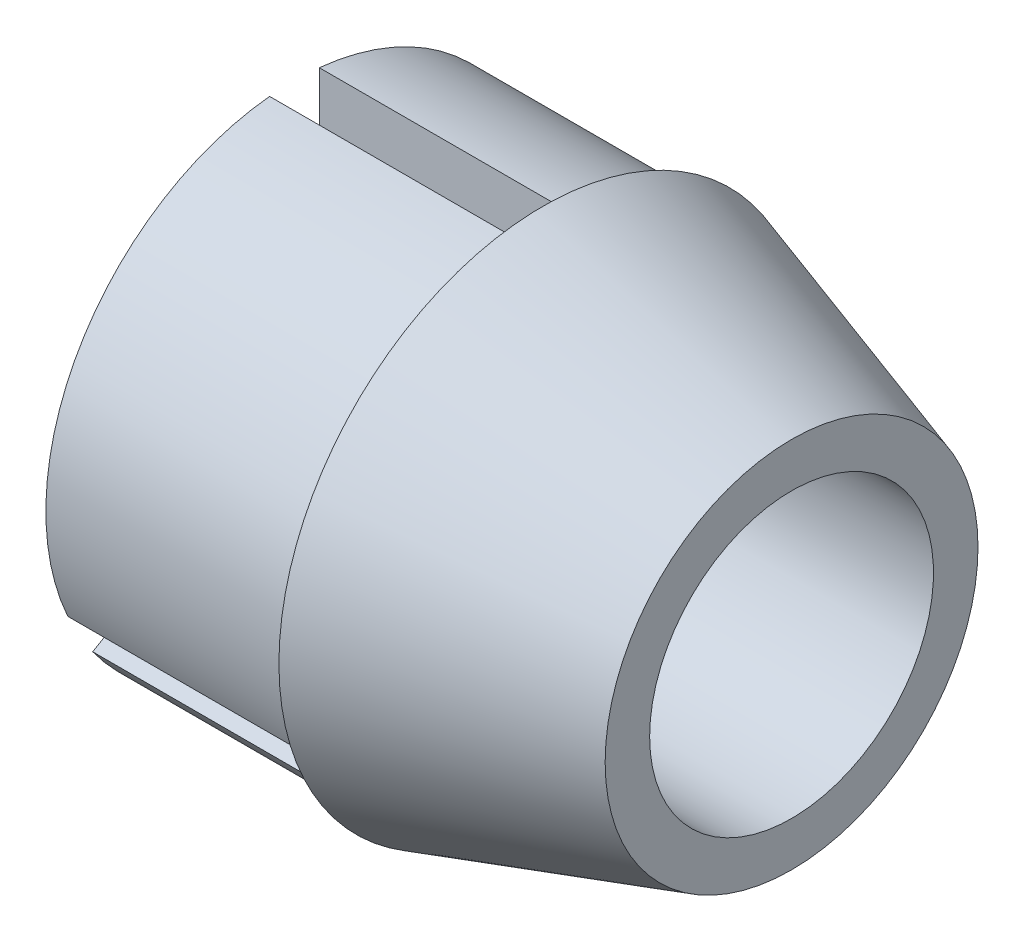
SolidWorks part; units mm, degrees
ref_plane "Front Plane" through (0, 0, 0) normal (0, 0, 1) x (1, 0, 0)
ref_plane "Top Plane" through (0, 0, 0) normal (0, 1, 0) x (1, 0, 0)
ref_plane "Right Plane" through (0, 0, 0) normal (1, 0, 0) x (0, 0, -1)
sketch "Sketch1" plane through (0, 0, 0) normal (0, 0, 1) x (1, 0, 0)
  line L0 (0, 14.5034) -> (25.4, 14.5034)
  line L1 (0, 14.5034) -> (0, 26.9875) construction
  line L2 (0, 26.9875) -> (25.4, 19.05)
  line L3 (25.4, 19.05) -> (25.4, 14.5034)
  line L4 (0, 26.9875) -> (0, 25.4)
  line L5 (0, 25.4) -> (-25.4, 25.4)
  line L6 (-25.4, 25.4) -> (-25.4, 16.0909)
  line L7 (-25.4, 16.0909) -> (0, 16.0909)
  line L8 (0, 16.0909) -> (0, 14.5034)
  dimension "D1" = 25.4
  dimension "D2" = 4.5466
  dimension "D3" = 26.9875
  dimension "D4" = 14.5034
  dimension "D5" = 1.5875
  dimension "D6" = 1.5875
  dimension "D7" = 25.4
ref_axis "Axis1" through (-1.27, 0, 0) along (1, 0, 0)
revolve "Revolve1" add sketch "Sketch1" angle 360 about axis through (-1.27, 0, 0) along (1, 0, 0)
sketch "Sketch2" plane through (-25.4, 0, 0) normal (-1, 0, 0) x (0, 0, 1)
  line L0 (28.7663, -13.6753) -> (6.7693, -0.9753)
  line L1 (-2.54, 31.75) -> (2.54, 31.75)
  line L2 (-2.54, 31.75) -> (-2.54, 6.35)
  line L3 (-2.54, 6.35) -> (2.54, 6.35)
  line L4 (2.54, 31.75) -> (2.54, 6.35)
  line L5 (-2.54, 31.75) -> (2.54, 6.35) construction
  line L6 (-2.54, 6.35) -> (2.54, 31.75) construction
  line L7 (28.7663, -13.6753) -> (26.2263, -18.0747)
  line L8 (26.2263, -18.0747) -> (4.2293, -5.3747)
  line L9 (6.7693, -0.9753) -> (4.2293, -5.3747)
  line L10 (-26.2263, -18.0747) -> (-4.2293, -5.3747)
  line L11 (-26.2263, -18.0747) -> (-28.7663, -13.6753)
  line L12 (-28.7663, -13.6753) -> (-6.7693, -0.9753)
  line L13 (-4.2293, -5.3747) -> (-6.7693, -0.9753)
  point P0 (0, 19.05)
  point P7 (0, 0)
  point P16 (0, 0)
  dimension "D1" = 5.08
  dimension "D2" = 25.4
  dimension "D3" = 6.35
  dimension "D4" = 3
extrude "Cut-Extrude1" cut sketch "Sketch2" against normal up to surface (25.4 mm away) up to face at (0, 0, 25.4)
